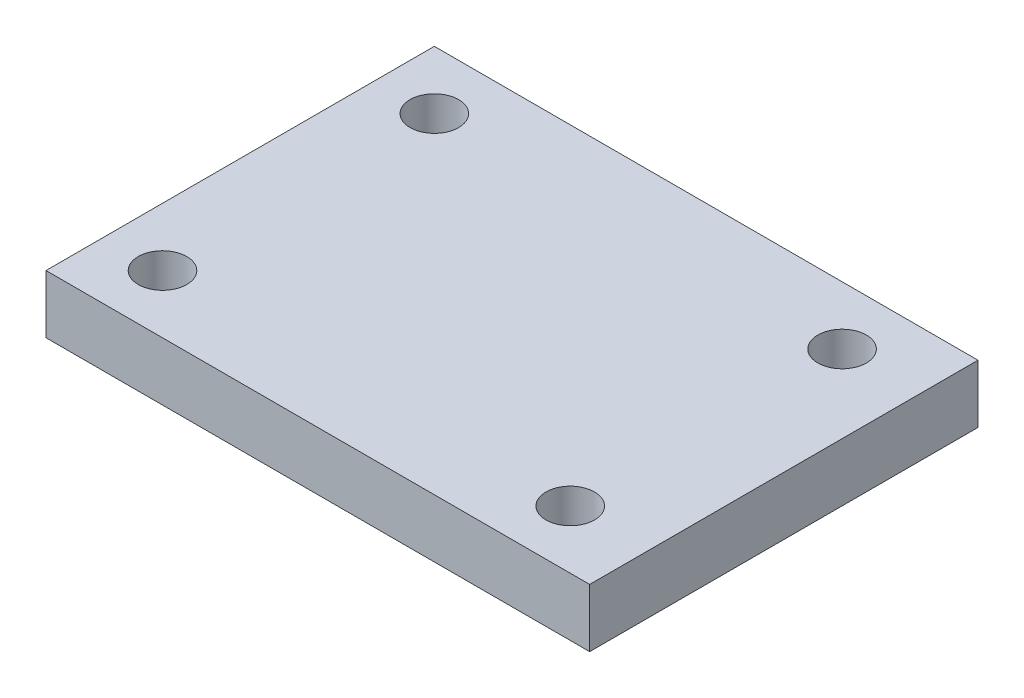
SolidWorks part; units mm, degrees
ref_plane "Ön Düzlem" through (0, 0, 0) normal (0, 0, 1) x (1, 0, 0)
ref_plane "Üst Düzlem" through (0, 0, 0) normal (0, 1, 0) x (1, 0, 0)
ref_plane "Sağ Düzlem" through (0, 0, 0) normal (1, 0, 0) x (0, 0, -1)
sketch "Sketch1" plane through (0, 0, 0) normal (0, 1, 0) x (1, 0, 0)
  line L1 (14, -10) -> (-14, -10)
  line L2 (14, -10) -> (14, 10)
  line L3 (14, 10) -> (-14, 10)
  line L4 (-14, -10) -> (-14, 10)
  line L5 (14, -10) -> (-14, 10) construction
  line L6 (14, 10) -> (-14, -10) construction
  point P0 (0, 0)
  dimension "D1" = 20
  dimension "D2" = 28
extrude "Boss-Extrude1" add sketch "Sketch1" along normal blind 3
hole_wizard "M3 Tapped Hole1" positions "Sketch2" profile "Sketch3" tap size "M3" standard "DIN" end condition through all
sketch "Sketch2" plane through (0, 3, 0) normal (0, 1, 0) x (1, 0, 0)
  line L0 (-14, 10) -> (-14, -10) construction
  line L1 (14, 10) -> (-14, 10) construction
  point P0 (-11, 7)
  point P2 (-11, -7)
  point P4 (10, -7)
  point P6 (10, 7)
  dimension "D1" = 14
  dimension "D2" = 21
  dimension "D3" = 3
  dimension "D4" = 3
sketch "Sketch3" plane through (-11, 3, -7) normal (1, 0, 0) x (0, 0, 1)
  line L0 (0, 0) -> (0, 3)
  line L1 (0, 3) -> (1.25, 3)
  line L2 (1.25, 3) -> (1.25, 0)
  line L5 (1.25, 0) -> (0, 0)
  line L11 (0, -6.35) -> (0, 107.95) construction
  dimension "Thru Tap Drill Dia." = 2.5
  dimension "Thru Tap Drill Depth" = 3
cosmetic thread "Hole Thread1"
cosmetic thread "Hole Thread2"
cosmetic thread "Hole Thread3"
cosmetic thread "Hole Thread4"
scale "Scale1" scale about centroid uniform scaling yes scale factor 1.5
